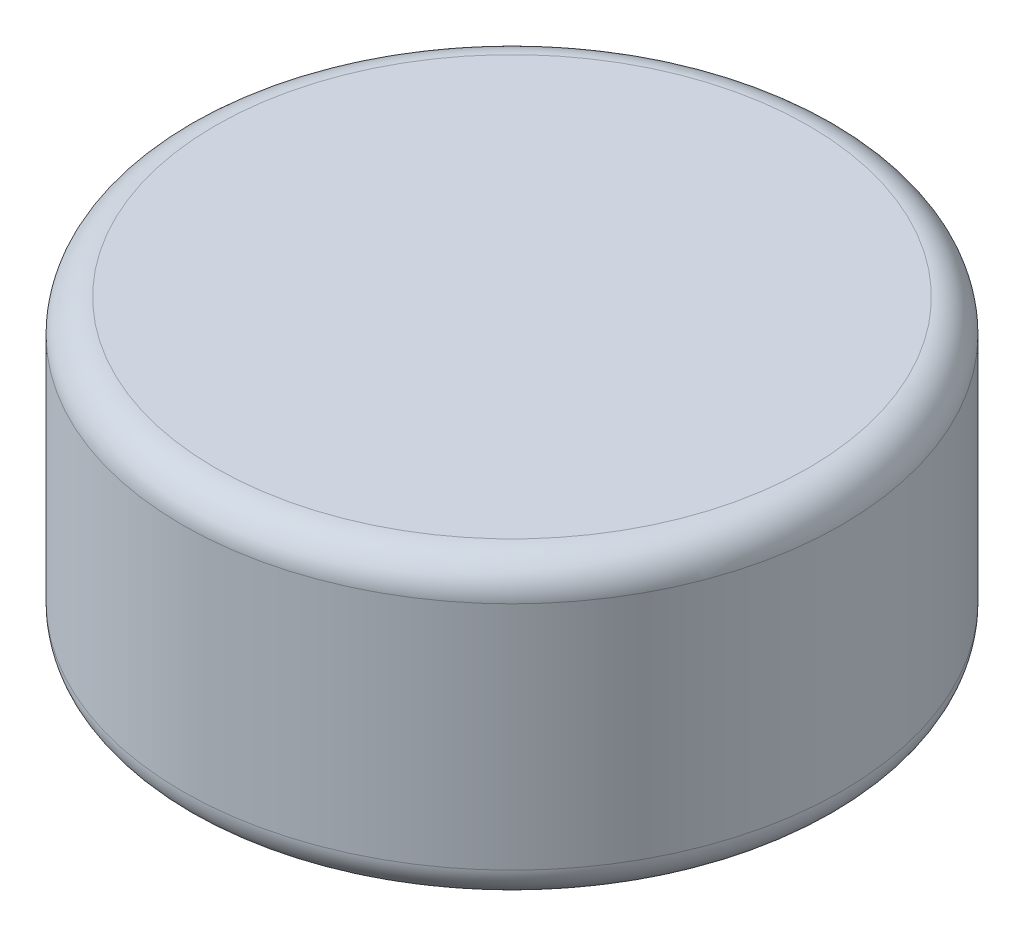
SolidWorks part; units mm, degrees
ref_plane "Front Plane" through (0, 0, 0) normal (0, 0, 1) x (1, 0, 0)
ref_plane "Top Plane" through (0, 0, 0) normal (0, 1, 0) x (1, 0, 0)
ref_plane "Right Plane" through (0, 0, 0) normal (1, 0, 0) x (0, 0, -1)
sketch "Sketch1" plane through (0, 0, 0) normal (0, 1, 0) x (1, 0, 0)
  circle A0 centre (0, 0) radius 2
  dimension "D1" = 4
extrude "Boss-Extrude1" add sketch "Sketch1" along normal blind 1.8
fillet "Fillet1" radius 0.2 2 edges at (0, 0, 2) (0, 1.8, 2)
